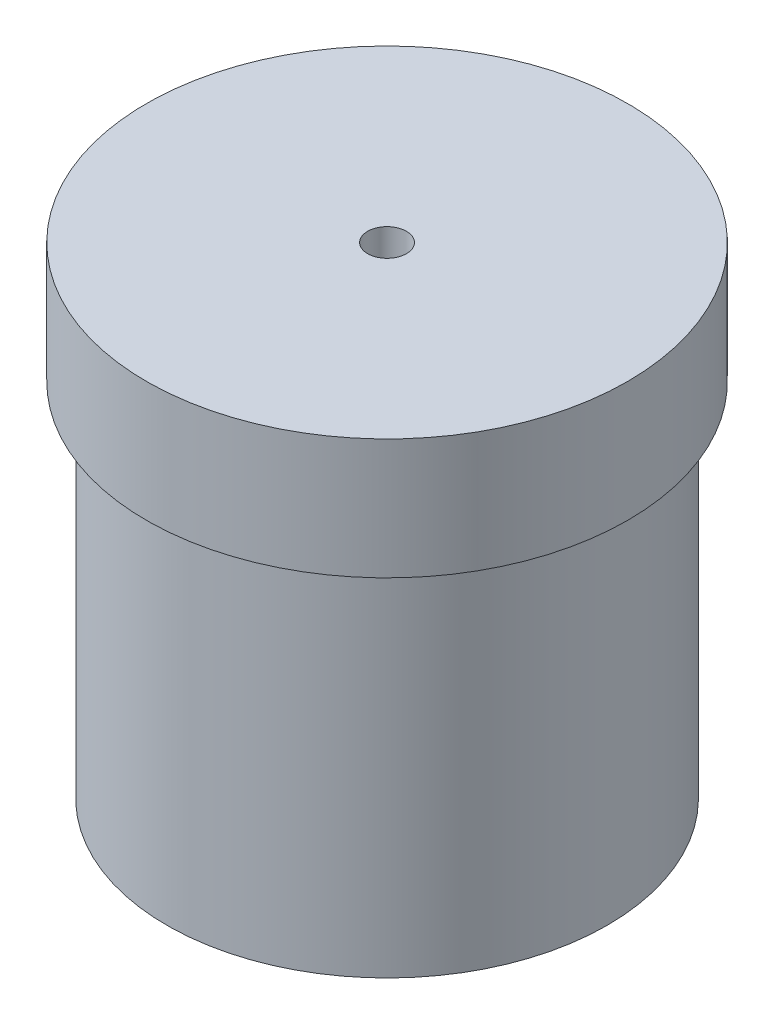
SolidWorks part; units mm, degrees
material "ABS"
ref_plane "Front Plane" through (0, 0, 0) normal (0, 0, 1) x (1, 0, 0)
ref_plane "Top Plane" through (0, 0, 0) normal (0, 1, 0) x (1, 0, 0)
ref_plane "Right Plane" through (0, 0, 0) normal (1, 0, 0) x (0, 0, -1)
sketch "Sketch1" plane through (0, 0, 0) normal (0, 0, 1) x (1, 0, 0)
  line L0 (0, 12.7) -> (-12.7, 12.7)
  line L1 (-12.7, 12.7) -> (-12.7, 6.35)
  line L2 (-12.7, 6.35) -> (-11.6205, 6.35)
  line L3 (-11.6205, 6.35) -> (-11.6205, -12.7)
  line L4 (-11.6205, -12.7) -> (0, -12.7)
  line L5 (0, -12.7) -> (0, 12.7) construction
  line L6 (0, 12.7) -> (0, -12.7)
  point P4 (0, 0)
  dimension "D1" = 11.6205
  dimension "D2" = 12.7
  dimension "D3" = 6.35
  dimension "D4" = 25.4
revolve "Revolve1" add sketch "Sketch1" angle 360 about L5
hole_wizard "M2.5x0.45 Tapped Hole1" positions "Sketch2" profile "Sketch3" tap size "M2.5x0.45" standard "ANSI Metric"
sketch "Sketch2" plane through (0, 12.7, 0) normal (0, 1, 0) x (1, 0, 0)
  point P0 (0, 0)
sketch "Sketch3" plane through (0, 12.7, 0) normal (1, 0, 0) x (0, 0, 1)
  line L0 (0, 0) -> (0, 6.9659)
  line L1 (0, 6.9659) -> (1.025, 6.35)
  line L2 (1.025, 6.35) -> (1.025, 0)
  line L5 (1.025, 0) -> (0, 0)
  line L10 (0, 6.9659) -> (-1.025, 6.35) construction
  line L11 (0, -6.35) -> (0, 107.95) construction
  dimension "Tap Drill Dia." = 2.05
  dimension "Tap Drill Depth" = 6.35
  dimension "Drill Angle" = 118
cosmetic thread "Hole Thread1" parameters "D1"=5.08, "D2"=2.5
